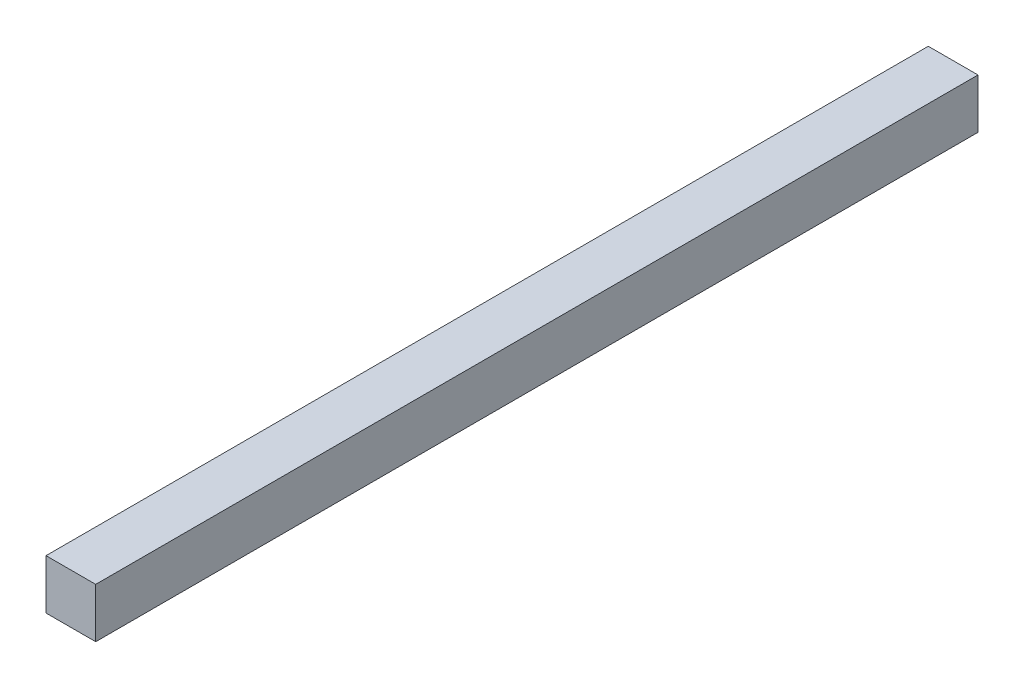
SolidWorks part; units mm, degrees
ref_plane "Front Plane" through (0, 0, 0) normal (0, 0, 1) x (1, 0, 0)
ref_plane "Top Plane" through (0, 0, 0) normal (0, 1, 0) x (1, 0, 0)
ref_plane "Right Plane" through (0, 0, 0) normal (1, 0, 0) x (0, 0, -1)
sketch "Sketch1" plane through (0, 0, 0) normal (0, 0, 1) x (1, 0, 0)
  line L1 (-25.4359, 25.2308) -> (14.5641, 25.2308)
  line L2 (-25.4359, 25.2308) -> (-25.4359, -14.7692)
  line L3 (-25.4359, -14.7692) -> (14.5641, -14.7692)
  line L4 (14.5641, 25.2308) -> (14.5641, -14.7692)
  dimension "D1" = 40
  dimension "D2" = 40
extrude "Boss-Extrude1" add sketch "Sketch1" along normal blind 710
